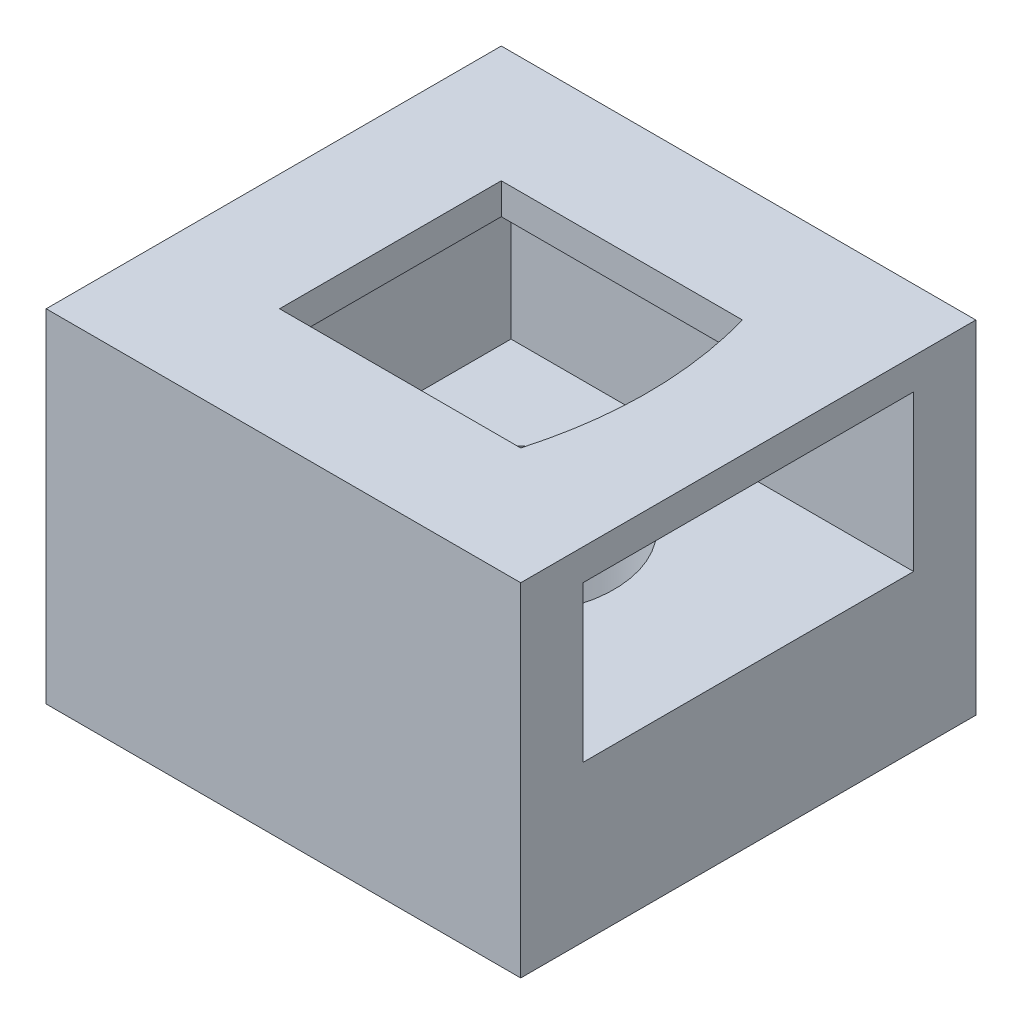
SolidWorks part; units mm, degrees
ref_plane "Front Plane" through (0, 0, 0) normal (0, 0, 1) x (1, 0, 0)
ref_plane "Top Plane" through (0, 0, 0) normal (0, 1, 0) x (1, 0, 0)
ref_plane "Right Plane" through (0, 0, 0) normal (1, 0, 0) x (0, 0, -1)
sketch "Sketch2" plane through (0, 0, 0) normal (0, 1, 0) x (1, 0, 0)
  line L1 (-3.1, -2.85) -> (3.1, -2.85)
  line L2 (-3.1, -2.85) -> (-3.1, 2.85)
  line L3 (-3.1, 2.85) -> (3.1, 2.85)
  line L4 (3.1, -2.85) -> (3.1, 2.85)
  line L5 (-3.1, -2.85) -> (3.1, 2.85) construction
  line L6 (-3.1, 2.85) -> (3.1, -2.85) construction
  line L7 (-6.1, 5.85) -> (6.1, 5.85)
  line L8 (-6.1, 5.85) -> (-6.1, -5.85)
  line L9 (-6.1, -5.85) -> (6.1, -5.85)
  line L10 (6.1, 5.85) -> (6.1, -5.85)
  line L11 (-6.1, 5.85) -> (6.1, -5.85) construction
  line L12 (-6.1, -5.85) -> (6.1, 5.85) construction
  circle A0 centre (0, 0) radius 2.65
  point P11 (0, 0)
  point P12 (0, 0)
  dimension "D1" = 5.3
  dimension "D2" = 5.7
  dimension "D3" = 6.2
  dimension "D4" = 3
  dimension "D5" = 3
extrude "Boss-Extrude1" add sketch "Sketch2" against normal blind 0.8 contours L10 L7 L8 L9 L4 L1 L2 L3
sketch "Sketch3" plane through (0, -0.8, 0) normal (0, -1, 0) x (1, 0, 0)
  line L1 (-4.25, 4.25) -> (4.25, 4.25)
  line L2 (-4.25, 4.25) -> (-4.25, -4.25)
  line L3 (-4.25, -4.25) -> (4.25, -4.25)
  line L4 (4.25, 4.25) -> (4.25, -4.25)
  line L5 (-4.25, 4.25) -> (4.25, -4.25) construction
  line L6 (-4.25, -4.25) -> (4.25, 4.25) construction
  line L7 (-6.1, 5.85) -> (6.1, 5.85)
  line L8 (-6.1, 5.85) -> (-6.1, -5.85)
  line L9 (-6.1, -5.85) -> (6.1, -5.85)
  line L10 (6.1, 5.85) -> (6.1, -5.85)
  line L11 (-6.1, 5.85) -> (6.1, -5.85) construction
  line L12 (-6.1, -5.85) -> (6.1, 5.85) construction
  point P0 (0, 0)
  point P6 (0, 0)
  dimension "D1" = 8.5
  dimension "D2" = 8.5
extrude "Boss-Extrude2" add sketch "Sketch3" along normal blind 4
sketch "Sketch4" plane through (0, -4.8, 0) normal (0, -1, 0) x (1, 0, 0)
  line L1 (-6.1, 5.85) -> (6.1, 5.85)
  line L2 (-6.1, 5.85) -> (-6.1, -5.85)
  line L3 (-6.1, -5.85) -> (6.1, -5.85)
  line L4 (6.1, 5.85) -> (6.1, -5.85)
  line L5 (-6.1, 5.85) -> (6.1, -5.85) construction
  line L6 (-6.1, -5.85) -> (6.1, 5.85) construction
  circle A0 centre (0, 0) radius 2.65
  dimension "D1" = 5.3
extrude "Boss-Extrude3" add sketch "Sketch4" along normal blind 4
sketch "Sketch5" plane through (0, -8.8, 0) normal (0, -1, 0) x (1, 0, 0)
  line L1 (-6.1, -5.85) -> (-3.6, -5.85)
  line L2 (-6.1, -5.85) -> (-6.1, -3.35)
  line L3 (-6.1, -3.35) -> (-3.6, -3.35)
  line L4 (-3.6, -5.85) -> (-3.6, -3.35)
  dimension "D1" = 2.5
  dimension "D2" = 2.5
extrude "Boss-Extrude4" add sketch "Sketch5" along normal blind 6.22
sketch "Sketch8" plane through (4.25, 0, 0) normal (-1, 0, 0) x (0, 0, 1)
  line L0 (-4.25, -4.8) -> (-4.25, -0.8) construction
  line L1 (-4.25, -0.8) -> (4.25, -0.8)
  line L2 (-4.25, -0.8) -> (-4.25, -4.8)
  line L3 (-4.25, -4.8) -> (4.25, -4.8)
  line L4 (4.25, -0.8) -> (4.25, -4.8)
  line L5 (-4.25, -0.8) -> (4.25, -0.8) construction
  line L6 (4.25, -4.8) -> (4.25, -0.8) construction
  line L7 (-4.25, -4.8) -> (4.25, -4.8) construction
  dimension "D1" = 0
  dimension "D2" = 0
  dimension "D3" = 0
  dimension "D4" = 0
extrude "Cut-Extrude2" cut sketch "Sketch8" against normal blind 6.22
sketch "Sketch9" plane through (0, 0, 0) normal (0, 1, 0) x (1, 0, 0)
  line L0 (3.1, -2.85) -> (3.1, 2.85) construction
  line L1 (3.1, 2.85) -> (3.1, -2.85)
  spline S0 degree 2 poles (3.1, 2.85) (3.9, 0) (3.1, -2.85) knots 0 0 0 1 1 1
  dimension "D1" = 0.4
extrude "Cut-Extrude3" cut sketch "Sketch9" against normal blind 2
